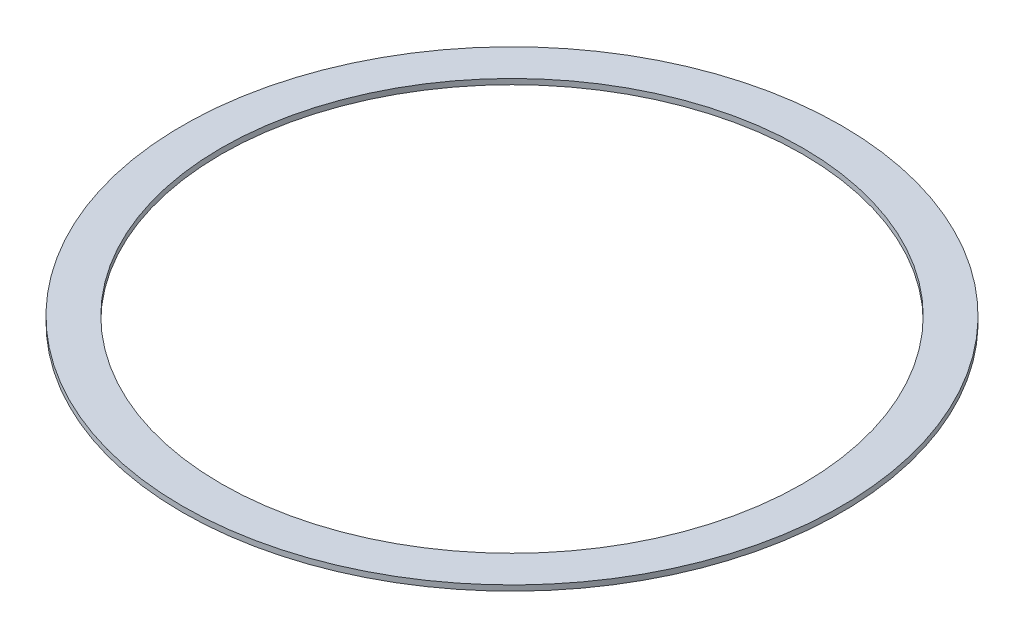
SolidWorks part; units mm, degrees
ref_plane "Front Plane" through (0, 0, 0) normal (0, 0, 1) x (1, 0, 0)
ref_plane "Top Plane" through (0, 0, 0) normal (0, 1, 0) x (1, 0, 0)
ref_plane "Right Plane" through (0, 0, 0) normal (1, 0, 0) x (0, 0, -1)
sketch "Sketch1" plane through (0, 0, 0) normal (0, 1, 0) x (1, 0, 0)
  circle A0 centre (0, 0) radius 42.5
  circle A1 centre (0, 0) radius 37.5
  point P3 (0, 0)
  dimension "D1" = 85
  dimension "D2" = 75
extrude "Boss-Extrude1" add sketch "Sketch1" along normal blind 0.7
